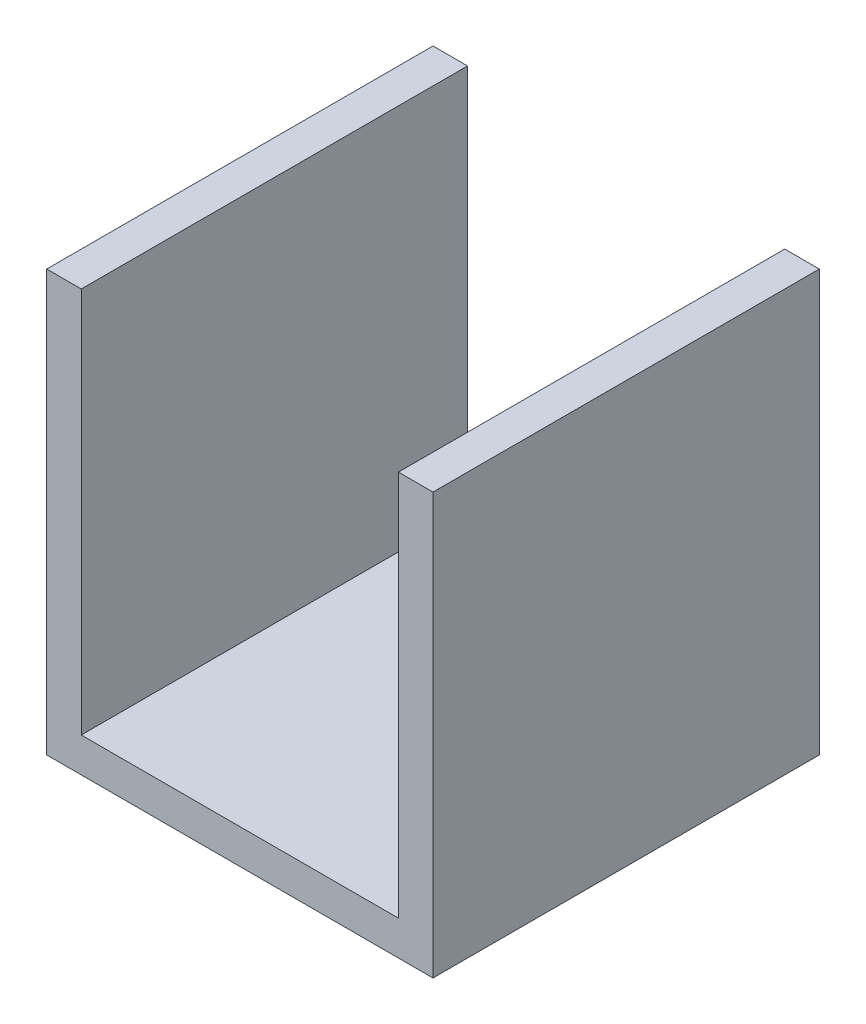
SolidWorks part; units mm, degrees
ref_plane "Front Plane" through (0, 0, 0) normal (0, 0, 1) x (1, 0, 0)
ref_plane "Top Plane" through (0, 0, 0) normal (0, 1, 0) x (1, 0, 0)
ref_plane "Right Plane" through (0, 0, 0) normal (1, 0, 0) x (0, 0, -1)
sketch "Sketch1" plane through (0, 0, 0) normal (0, 1, 0) x (1, 0, 0)
  line L0 (0, 0) -> (88.9, 0)
  line L1 (88.9, 0) -> (88.9, 88.9)
  line L2 (88.9, 88.9) -> (0, 88.9)
  line L3 (0, 88.9) -> (0, 0)
  dimension "D1" = 88.9
  dimension "D2" = 88.9
extrude "Boss-Extrude1" add sketch "Sketch1" along normal blind 7.9502
sketch "Sketch2" plane through (0, 0, 0) normal (0, 1, 0) x (1, 0, 0)
  line L0 (0, 0) -> (7.9502, 0)
  line L1 (0, 0) -> (88.9, 0) construction
  line L2 (7.9502, 0) -> (7.9502, 88.9)
  line L3 (88.9, 88.9) -> (0, 88.9) construction
  line L4 (7.9502, 88.9) -> (0, 88.9)
  line L5 (0, 88.9) -> (0, 0)
  line L6 (88.9, 0) -> (80.9498, 0)
  line L7 (80.9498, 0) -> (80.9498, 88.9)
  line L8 (80.9498, 88.9) -> (88.9, 88.9)
  line L9 (88.9, 88.9) -> (88.9, 0)
  dimension "D1" = 7.9502
  dimension "D2" = 7.9502
extrude "Boss-Extrude2" add sketch "Sketch2" along normal blind 96.8502
sketch "Sketch4" plane through (80.9498, 0, 0) normal (-1, 0, 0) x (0, 0, 1)
  line L0 (-88.9, 96.8502) -> (0, 96.8502) construction
  circle A0 centre (-44.45, 96.8502) radius 9.459
